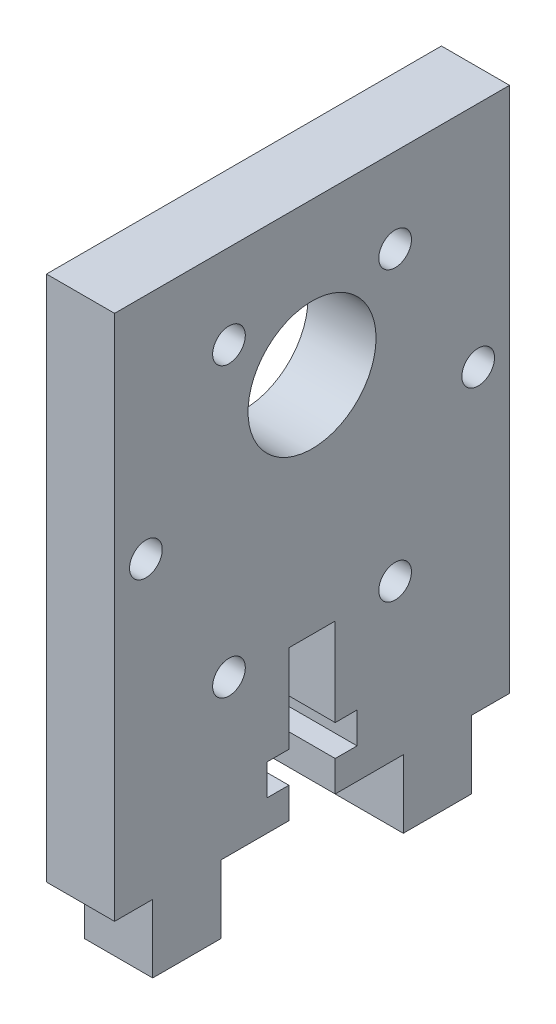
SolidWorks part; units mm, degrees
ref_plane "Front Plane" through (0, 0, 0) normal (0, 0, 1) x (1, 0, 0)
ref_plane "Top Plane" through (0, 0, 0) normal (0, 1, 0) x (1, 0, 0)
ref_plane "Right Plane" through (0, 0, 0) normal (1, 0, 0) x (0, 0, -1)
sketch "Motor plate" plane through (0, 0, 0) normal (1, 0, 0) x (0, 0, -1)
  line L0 (0, 3.2604) -> (7.747, 16.6786) construction
  line L1 (-18.415, -24.5526) -> (-14.859, -24.5526)
  line L2 (-18.415, -24.5526) -> (-18.415, 24.5526)
  line L3 (-18.415, 24.5526) -> (18.415, 24.5526)
  line L4 (18.415, -24.5526) -> (18.415, 24.5526)
  line L5 (-18.415, -24.5526) -> (18.415, 24.5526) construction
  line L6 (-18.415, 24.5526) -> (18.415, -24.5526) construction
  line L7 (14.859, -24.5526) -> (18.415, -24.5526)
  line L13 (0, 24.5526) -> (0, -24.5526) construction
  circle A0 centre (7.747, 16.6786) radius 1.524
  circle A1 centre (15.494, 3.2604) radius 1.524
  circle A2 centre (7.747, -10.1578) radius 1.524
  circle A3 centre (-7.747, -10.1578) radius 1.524
  circle A4 centre (-15.494, 3.2604) radius 1.524
  circle A5 centre (-7.747, 16.6786) radius 1.524
  circle A6 centre (0, 10.3724) radius 5.969
  circle A7 centre (0, 3.2604) radius 18.415 construction
  point P0 (0, 0)
  point P13 (0, -15.1546)
  point P15 (0, 3.2604)
  point P32 (0, 3.2604)
  line B0 (-8.509, -24.5526) -> (-8.509, -30.9026)
  line B1 (-8.509, -30.9026) -> (-14.859, -30.9026)
  line B2 (-14.859, -30.9026) -> (-14.859, -24.5526)
  line B3 (-2.159, -24.5526) -> (-2.159, -21.6849)
  line B4 (-2.159, -21.6849) -> (-4.2, -21.6849)
  line B5 (-4.2, -21.6849) -> (-4.2, -18.7849)
  line B6 (-4.2, -18.7849) -> (-2.159, -18.7849)
  line B7 (-2.159, -18.7849) -> (-2.159, -10.5826)
  line B8 (-2.159, -10.5826) -> (2.159, -10.5826)
  line B9 (2.159, -10.5826) -> (2.159, -18.7849)
  line B10 (2.159, -18.7849) -> (4.2, -18.7849)
  line B11 (4.2, -18.7849) -> (4.2, -21.6849)
  line B12 (4.2, -21.6849) -> (2.159, -21.6849)
  line B13 (2.159, -21.6849) -> (2.159, -24.5526)
  line B14 (0, -10.5826) -> (0, -24.5526) construction
  line B15 (8.509, -24.5526) -> (2.159, -24.5526)
  line B16 (14.859, -30.9026) -> (14.859, -24.5526)
  line B17 (-8.509, -24.5526) -> (-2.159, -24.5526)
  line B18 (8.509, -30.9026) -> (14.859, -30.9026)
  line B19 (8.509, -24.5526) -> (8.509, -30.9026)
  dimension "D3" = 30
  dimension "D4" = 15.494
  dimension "D5" = 3.048
  dimension "D8" = 11.938
  dimension "D2" = 36.83
  dimension "D1" = 9.398
  dimension "D6" = 6.35
  dimension "D7" = 6
  dimension "D9" = 7.112
sketch_block_instance "Male T-slot assembly-1"
sketch_block "Male T-slot assembly" parameters "D1"=6.35, "D2"=6.35, "D3"=4.318, "D4"=2.9, "D5"=8.4, "D6"=13.97, "D7"=6.35
extrude "Boss-Extrude1" add sketch "Motor plate" along normal blind 6.35
equation "\"Ball Diameter\"= 1.75in"
equation "\"Sheet Thickness\"= 0.25in"
equation "\"Screw Diameter\"= .17in"
equation "\"Robot Diameter\"= 14in"
equation "\"Castor Screw Diameter\"= 0.22in"
equation "\"Wheel Diameter\" = 4in"
equation "\"Nut Diameter\" = 8.4mm"
equation "\"Nut Height\" = 2.9mm"
equation "\"Screw Height\" = 0.55in"
equation "\"D1@Boss-Extrude1\"=\"Sheet Thickness\""
equation "\"Ball Radius\" = \"Ball Diameter\"/2"
equation "\"Pulley Diameter\" = 1in"
equation "\"Reactor Height\" = 14in"
equation "\"Elevator Height\" = 11.5in"
equation "\"Elevator Width\" = \"Ball Diameter\" + 0.25in"
equation "\"Elevator Bearing Diameter\" = sqr(2*(\"Sheet Thickness\"^2)) + 0.2in"
equation "\"Elevator Axle Endcap Diameter\" = \"Pulley Diameter\" + 0.25in"
equation "\"Elevator Axle Length\" = \"Elevator Width\" + 8*\"Sheet Thickness\""
equation "\"Elevator Clearance from Axis\" = 3.28in"
equation "\"Elevator Horizontal Clearance\" = \"Elevator Width\" + 0.5in"
equation "\"Claw Horizontal Seperation\" = (\"Elevator Width\"/2) - (1.5 * \"Sheet Thickness\") - 0.15in"
equation "\"Claw Radius\" = \"Ball Radius\" + 0.1in"
equation "\"Castor Wheel Height\" = 1.25in"
